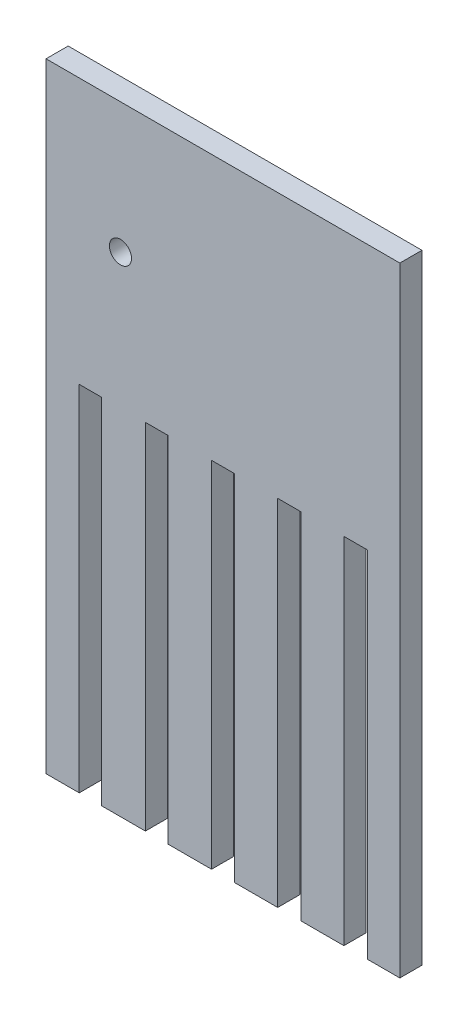
SolidWorks part; units mm, degrees
material "Custom Plastic"
ref_plane "X-Y Datum" through (0, 0, 0) normal (0, 0, 1) x (1, 0, 0)
ref_plane "X-Z Datum" through (0, 0, 0) normal (0, 1, 0) x (1, 0, 0)
ref_plane "Y-Z Datum" through (0, 0, 0) normal (1, 0, 0) x (0, 0, -1)
sketch "Sketch1" plane through (0, 0, 0) normal (0, 0, 1) x (1, 0, 0)
  line L0 (0, 44.45) -> (0, -44.45)
  line L1 (-25.4, 44.45) -> (25.4, 44.45)
  line L2 (-25.4, 44.45) -> (-25.4, -44.45)
  line L3 (-25.4, -44.45) -> (25.4, -44.45)
  line L4 (25.4, 44.45) -> (25.4, -44.45)
  line L5 (-25.4, 44.45) -> (25.4, -44.45) construction
  line L6 (-25.4, -44.45) -> (25.4, 44.45) construction
  line L8 (-1.5875, 6.35) -> (1.5875, 6.35)
  line L9 (-1.5875, 6.35) -> (-1.5875, -44.45)
  line L10 (-1.5875, -44.45) -> (1.5875, -44.45)
  line L11 (1.5875, 6.35) -> (1.5875, -44.45)
  line L12 (-1.5875, 6.35) -> (1.5875, -44.45) construction
  line L13 (-1.5875, -44.45) -> (1.5875, 6.35) construction
  line L19 (-1.5875, 6.35) -> (-1.5875, -44.45)
  line L20 (-1.5875, 6.35) -> (1.5875, 6.35)
  line L21 (1.5875, 6.35) -> (1.5875, -44.45)
  line L28 (-1.5875, 6.35) -> (-1.5875, -44.45)
  line L29 (-1.5875, 6.35) -> (1.5875, 6.35)
  line L30 (1.5875, 6.35) -> (1.5875, -44.45)
  line L37 (8.2245, 6.35) -> (8.2245, -44.45) [skipped]
  line L38 (8.2245, 6.35) -> (11.3995, 6.35) [skipped]
  line L39 (8.2245, 6.35) -> (8.2245, -44.45) [skipped]
  line L40 (8.2245, 6.35) -> (11.3995, 6.35) [skipped]
  line L41 (11.3995, 6.35) -> (11.3995, -44.45) [skipped]
  line L42 (11.3995, 6.35) -> (11.3995, -44.45) [skipped]
  line L43 (18.0364, 6.35) -> (18.0364, -44.45) [skipped]
  line L44 (18.0364, 6.35) -> (21.2114, 6.35) [skipped]
  line L45 (21.2114, 6.35) -> (21.2114, -44.45) [skipped]
  line L46 (-11.3995, 6.35) -> (-11.3995, -44.45) [skipped]
  line L47 (-8.2245, 6.35) -> (-8.2245, -44.45) [skipped]
  line L48 (-11.3995, 6.35) -> (-11.3995, -44.45) [skipped]
  line L49 (-8.2245, 6.35) -> (-8.2245, -44.45) [skipped]
  line L50 (-11.3995, 6.35) -> (-8.2245, 6.35) [skipped]
  line L51 (-11.3995, 6.35) -> (-8.2245, 6.35) [skipped]
  line L52 (-18.0364, 6.35) -> (-18.0364, -44.45) [skipped]
  line L53 (-21.2114, 6.35) -> (-21.2114, -44.45) [skipped]
  line L54 (-21.2114, 6.35) -> (-18.0364, 6.35) [skipped]
  circle A0 centre (-14.7158, 25.7526) radius 1.5875
  point P0 (0, 0)
  point P8 (0, -19.05)
  point P13 (-17.1048, 29.9334)
  point P16 (-13.9418, 24.3981)
  point P17 (0, 0)
  point P18 (-14.7158, 25.7526)
  point P27 (0, 0)
  point P29 (0, 0)
  point P34 (0, 0)
  dimension "D7" = 3.175
  dimension "D1" = 3.175
  dimension "D2" = 50.8
  dimension "D3" = 88.9
  dimension "D4" = 50.8
  dimension "D5" = 3
  dimension "D6" = 3
extrude "Boss-Extrude1" add sketch "Sketch1" along normal blind 3.175 contours L8 L11 L3 L4 L1 L0 | L9 L8 L0 L1 L2 L3 A0 | L11 L8 L0 L3 | L8 L9 L3 L0
sketch "Sketch2" plane through (0, 0, 3.175) normal (0, 0, 1) x (1, 0, 0)
  line L4 (1.5875, 6.35) -> (-1.5875, 6.35)
  line L5 (1.5875, -44.45) -> (1.5875, 6.35)
  line L6 (-1.5875, -44.45) -> (1.5875, -44.45)
  line L7 (-1.5875, 6.35) -> (-1.5875, -44.45)
  line L8 (1.5875, 6.35) -> (-1.5875, 6.35)
  line L9 (1.5875, -44.45) -> (1.5875, 6.35)
  line L10 (-1.5875, -44.45) -> (1.5875, -44.45)
  line L11 (-1.5875, 6.35) -> (-1.5875, -44.45)
  line L12 (25.4, 44.45) -> (-25.4, 44.45)
  line L13 (25.4, -44.45) -> (25.4, 44.45)
  line L14 (-25.4, -44.45) -> (25.4, -44.45)
  line L15 (-25.4, 44.45) -> (-25.4, -44.45)
  line L16 (25.4, 44.45) -> (-25.4, 44.45)
  line L17 (25.4, -44.45) -> (25.4, 44.45)
  line L18 (-25.4, -44.45) -> (25.4, -44.45)
  line L19 (-25.4, 44.45) -> (-25.4, -44.45)
  circle A1 centre (-14.7158, 25.7526) radius 1.5875
  circle A2 centre (-14.7158, 25.7526) radius 1.5875
  line M11 (-25.4, -44.45) -> (25.4, -44.45)
  dimension "D1" = 0
  dimension "D2" = 0
  dimension "D3" = 0
extrude "Cut-Extrude1" cut sketch "Sketch2" against normal through all contours L8 L11 L9 M11
pattern_linear "LPattern1" count 3 spacing 9.525 along (1, 0, 0) count 3 spacing 9.525 along (-1, 0, 0) of "Cut-Extrude1"
sketch "Sketch3" plane through (0, 0, 3.175) normal (0, 0, 1) x (1, 0, 0)
  line L0 (-11.1379, -44.45) -> (-11.1379, 6.3754)
  line L1 (-11.1379, 6.3754) -> (-7.9121, 6.3754)
  line L2 (-7.9121, 6.3754) -> (-7.9121, -44.45)
  line L3 (-1.6383, -44.45) -> (-1.6383, 6.4008)
  line L4 (-1.6383, 6.4008) -> (1.6383, 6.4008)
  line L5 (1.6383, 6.4008) -> (1.6383, -44.45)
  line L6 (7.8613, -44.45) -> (7.8613, 6.4262)
  line L7 (7.8613, 6.4262) -> (11.1887, 6.4262)
  line L8 (11.1887, 6.4262) -> (11.1887, -44.45)
  line L9 (17.3609, -44.45) -> (17.3609, 6.4516)
  line L10 (17.3609, 6.4516) -> (20.7391, 6.4516)
  line L11 (20.7391, 6.4516) -> (20.7391, -44.45)
  line L24 (-17.4625, 6.35) -> (-17.4625, -44.45)
  line L25 (-17.4625, -44.45) -> (-11.1125, -44.45)
  line L26 (-11.1125, -44.45) -> (-11.1125, 6.35)
  line L27 (-11.1125, 6.35) -> (-7.9375, 6.35)
  line L28 (-7.9375, 6.35) -> (-7.9375, -44.45)
  line L29 (-7.9375, -44.45) -> (-1.5875, -44.45)
  line L30 (-1.5875, -44.45) -> (-1.5875, 6.35)
  line L31 (-1.5875, 6.35) -> (1.5875, 6.35)
  line L32 (1.5875, 6.35) -> (1.5875, -44.45)
  line L33 (1.5875, -44.45) -> (7.9375, -44.45)
  line L34 (7.9375, -44.45) -> (7.9375, 6.35)
  line L35 (7.9375, 6.35) -> (11.1125, 6.35)
  line L36 (11.1125, 6.35) -> (11.1125, -44.45)
  line L37 (11.1125, -44.45) -> (17.4625, -44.45)
  line L38 (17.4625, -44.45) -> (17.4625, 6.35)
  line L39 (17.4625, 6.35) -> (20.6375, 6.35)
  line L40 (20.6375, 6.35) -> (20.6375, -44.45)
  line L41 (20.6375, -44.45) -> (25.4, -44.45)
  line L42 (25.4, -44.45) -> (25.4, 44.45)
  line L43 (25.4, 44.45) -> (-25.4, 44.45)
  line L44 (-25.4, 44.45) -> (-25.4, -44.45)
  line L45 (-25.4, -44.45) -> (-20.6375, -44.45)
  line L46 (-20.6375, -44.45) -> (-20.6375, 6.35)
  line L47 (-20.6375, 6.35) -> (-17.4625, 6.35)
  line L48 (-17.4625, 6.35) -> (-17.4625, -44.45)
  line L49 (-17.4625, -44.45) -> (-11.1125, -44.45)
  line L50 (-11.1125, -44.45) -> (-11.1125, 6.35)
  line L51 (-11.1125, 6.35) -> (-7.9375, 6.35)
  line L52 (-7.9375, 6.35) -> (-7.9375, -44.45)
  line L53 (-7.9375, -44.45) -> (-1.5875, -44.45)
  line L54 (-1.5875, -44.45) -> (-1.5875, 6.35)
  line L55 (-1.5875, 6.35) -> (1.5875, 6.35)
  line L56 (1.5875, 6.35) -> (1.5875, -44.45)
  line L57 (1.5875, -44.45) -> (7.9375, -44.45)
  line L58 (7.9375, -44.45) -> (7.9375, 6.35)
  line L59 (7.9375, 6.35) -> (11.1125, 6.35)
  line L60 (11.1125, 6.35) -> (11.1125, -44.45)
  line L61 (11.1125, -44.45) -> (17.4625, -44.45)
  line L62 (17.4625, -44.45) -> (17.4625, 6.35)
  line L63 (17.4625, 6.35) -> (20.6375, 6.35)
  line L64 (20.6375, 6.35) -> (20.6375, -44.45)
  line L65 (20.6375, -44.45) -> (25.4, -44.45)
  line L66 (25.4, -44.45) -> (25.4, 44.45)
  line L67 (25.4, 44.45) -> (-25.4, 44.45)
  line L68 (-25.4, 44.45) -> (-25.4, -44.45)
  line L69 (-25.4, -44.45) -> (-20.6375, -44.45)
  line L70 (-20.6375, -44.45) -> (-20.6375, 6.35)
  line L71 (-20.6375, 6.35) -> (-17.4625, 6.35)
  line M26 (-17.4625, -44.45) -> (-11.1125, -44.45)
  line M27 (-11.1125, -44.45) -> (-11.1125, 6.35)
  line M28 (-11.1125, 6.35) -> (-7.9375, 6.35)
  line M29 (-7.9375, 6.35) -> (-7.9375, -44.45)
  line M30 (-7.9375, -44.45) -> (-1.5875, -44.45)
  line M31 (-1.5875, -44.45) -> (-1.5875, 6.35)
  line M32 (-1.5875, 6.35) -> (1.5875, 6.35)
  line M33 (1.5875, 6.35) -> (1.5875, -44.45)
  line M34 (1.5875, -44.45) -> (7.9375, -44.45)
  line M35 (7.9375, -44.45) -> (7.9375, 6.35)
  line M36 (7.9375, 6.35) -> (11.1125, 6.35)
  line M37 (11.1125, 6.35) -> (11.1125, -44.45)
  line M38 (11.1125, -44.45) -> (17.4625, -44.45)
  line M39 (17.4625, -44.45) -> (17.4625, 6.35)
  line M40 (17.4625, 6.35) -> (20.6375, 6.35)
  line M41 (20.6375, 6.35) -> (20.6375, -44.45)
  line M42 (20.6375, -44.45) -> (25.4, -44.45)
  dimension "D1" = 0
  dimension "D2" = 0.0254
  dimension "D3" = 0.0508
  dimension "D4" = 0.0762
  dimension "D5" = 0.1016
extrude "Cut-Extrude2" cut sketch "Sketch3" against normal through all contours L2 L1 L0 M26 M27 M28 M29 M30 | L5 L4 L3 M30 M31 M32 M33 M34 | L8 L7 L6 M34 M35 M36 M37 M38 | L11 L10 L9 M38 M39 M40 M41 M42
